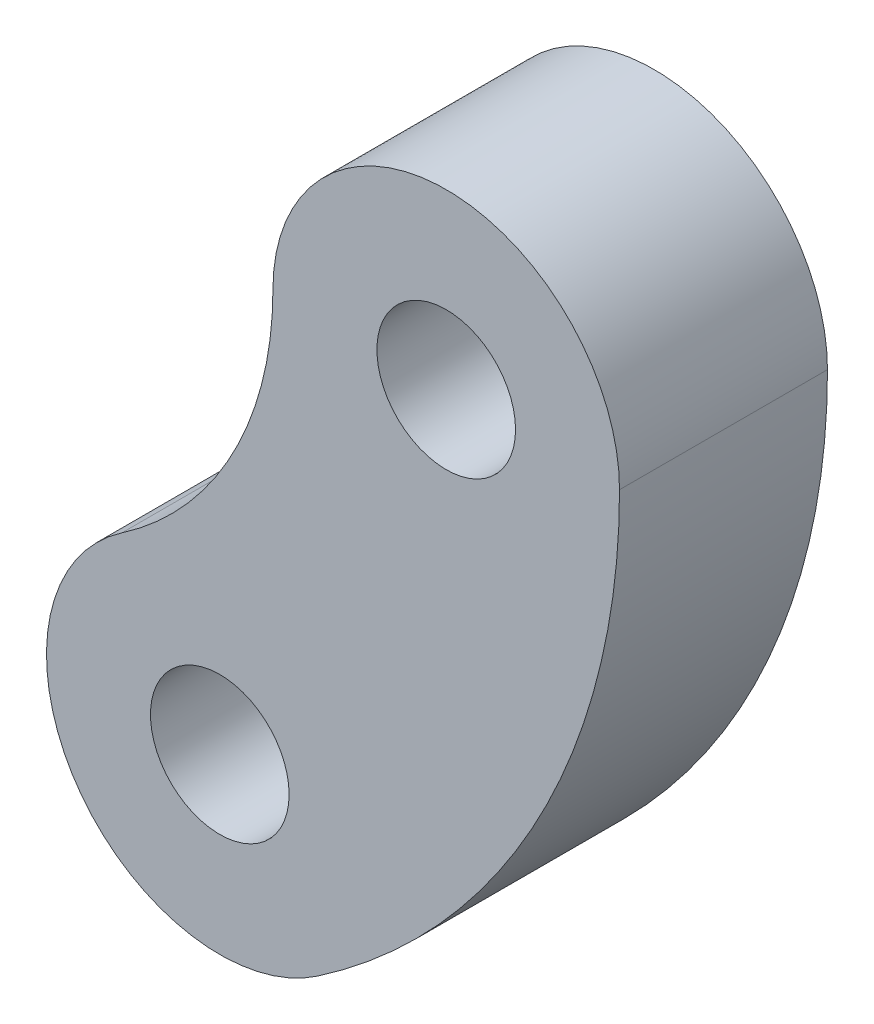
SolidWorks part; units mm, degrees
ref_plane "Front Plane" through (0, 0, 0) normal (0, 0, 1) x (1, 0, 0)
ref_plane "Top Plane" through (0, 0, 0) normal (0, 1, 0) x (1, 0, 0)
ref_plane "Right Plane" through (0, 0, 0) normal (1, 0, 0) x (0, 0, -1)
sketch "Sketch1" plane through (0, 0, 0) normal (0, 0, 1) x (1, 0, 0)
  arc A0 (5.6444, -8.2547) -> (10, 0) centre (0, 0) ccw
  arc A1 (2.8222, -4.1274) -> (5, 0) centre (0, 0) ccw
  arc A2 (10, 0) -> (5, 0) centre (7.5, 0) ccw
  arc A3 (2.8222, -4.1274) -> (5.6444, -8.2547) centre (4.2333, -6.191) ccw
  circle A4 centre (4.2333, -6.191) radius 1
  circle A5 centre (7.5, 0) radius 1
  dimension "D1" = 20
  dimension "D2" = 10
  dimension "D3" = 2
  dimension "D4" = 2
  dimension "D5" = 7
extrude "Boss-Extrude1" add sketch "Sketch1" along normal mid plane 3
